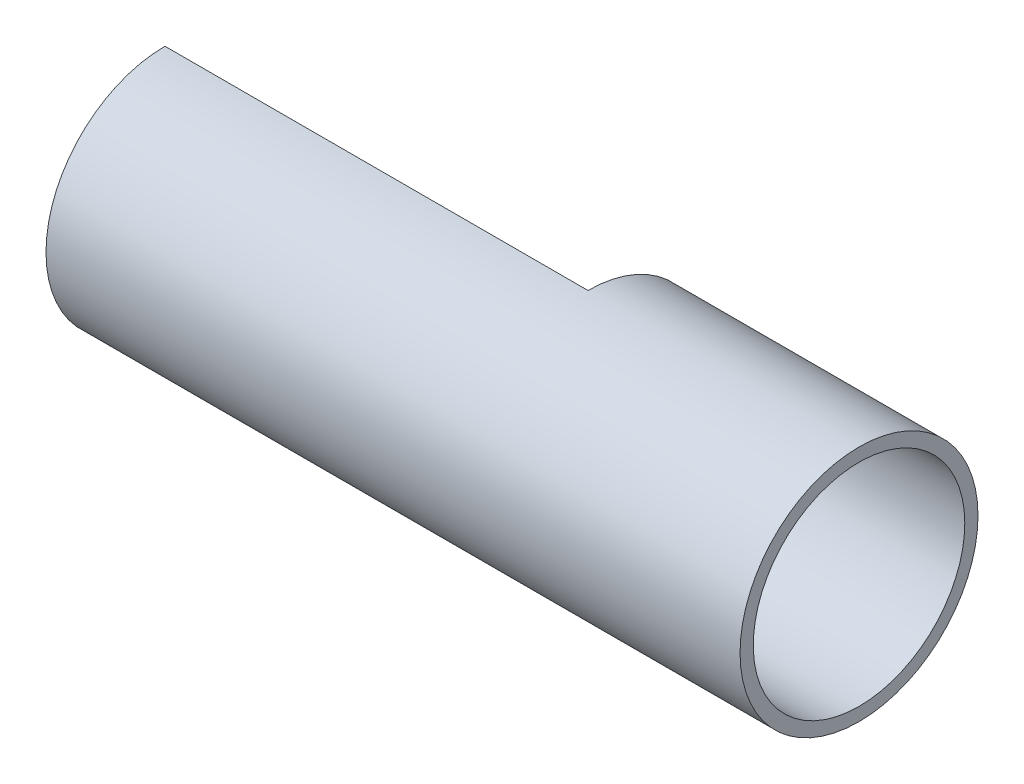
SolidWorks part; units mm, degrees
material "PET"
ref_plane "Front Plane" through (0, 0, 0) normal (0, 0, 1) x (1, 0, 0)
ref_plane "Top Plane" through (0, 0, 0) normal (0, 1, 0) x (1, 0, 0)
ref_plane "Right Plane" through (0, 0, 0) normal (1, 0, 0) x (0, 0, -1)
ref_axis "Axis1" through (88.99, 0, 0) along (-1, 0, 0)
sketch "Sketch1" plane through (0, 0, 0) normal (1, 0, 0) x (0, 0, -1)
  circle A0 centre (0, 0) radius 11.43
  dimension "D1" = 22.86
extrude "Main Shaft" add sketch "Sketch1" along normal mid plane 66.675
sketch "Sketch3" plane through (-33.3375, 0, 0) normal (-1, 0, 0) x (0, 0, 1)
  circle A0 centre (0, 0) radius 6.35
  dimension "D1" = 12.7
sketch "Sketch4" plane through (0, 0, 0) normal (0, 0, 1) x (1, 0, 0)
  line L0 (-33.3375, 6.35) -> (-33.3375, -6.35) construction
  line L1 (-33.3375, 0) -> (-33.3375, 6.35)
  line L2 (-39.6875, 0) -> (-33.3375, 0)
  arc A0 (-33.3375, 6.35) -> (-39.6875, 0) centre (-33.3375, 0) ccw
  dimension "D1" = 6.35
revolve "Bumpout" add sketch "Sketch4" angle 360 about axis through (88.99, 0, 0) along (-1, 0, 0)
sketch "Sketch5" plane through (-33.3375, 0, 0) normal (-1, 0, 0) x (0, 0, 1)
  circle A0 centre (0, 0) radius 1.27
  dimension "D1" = 2.54
extrude "Needle Hole" cut sketch "Sketch5" along normal through all both and the other way through all
ref_plane "Plane1" through (-30.7975, 0, 0) normal (-1, 0, 0) x (0, 0, 1)
sketch "Sketch7" plane through (-30.7975, 0, 0) normal (-1, 0, 0) x (0, 0, 1)
  circle A0 centre (0, 0) radius 10.16
  circle A1 centre (0, 0) radius 11.43 construction
  dimension "D1" = 1.27
extrude "Syringe Slot" cut sketch "Sketch7" against normal blind 40.132
sketch "Sketch9" plane through (33.3375, 0, 0) normal (1, 0, 0) x (0, 0, -1)
  circle A0 centre (0, 0) radius 10.16
  circle A2 centre (0, 0) radius 11.43 construction
  dimension "D1" = 1.27
  dimension "D2" = 20.32
extrude "Spring Slot" cut sketch "Sketch9" against normal offset from surface (22.733 mm away) 1.27 up to face at (9.3345, 0, 1.27)
sketch "Sketch11" plane through (10.6045, 0, 0) normal (1, 0, 0) x (0, 0, -1)
  line L0 (0, 12.573) -> (0, -12.573) construction
  line L1 (0, 0) -> (-1.27, 0) construction
  line L2 (-1.27, 8.7988) -> (-1.27, 0) construction
  line L3 (-1.27, 0) -> (-1.27, -8.7988) construction
  line L4 (-1.27, 8.7988) -> (-1.4514, 10.0558)
  line L5 (1.27, 8.7988) -> (1.4514, 10.0558)
  line L6 (-1.4514, -10.0558) -> (-1.27, -8.7988)
  line L7 (1.27, -8.7988) -> (1.4514, -10.0558)
  arc A0 (-1.4514, 10.0558) -> (-1.4514, -10.0558) centre (0, 0) ccw
  arc A1 (-1.27, 8.7988) -> (-1.27, -8.7988) centre (0, 0) ccw
  circle A2 centre (0, 0) radius 8.89
  circle A3 centre (0, 0) radius 8.89 construction
  arc A4 (1.27, 8.7988) -> (1.27, -8.7988) centre (0, 0) cw
  arc A5 (1.4514, 10.0558) -> (1.4514, -10.0558) centre (0, 0) cw
  dimension "D2" = 1.27
  dimension "D1" = 1.27
  dimension "D3" = 1.27
  dimension "D4" = 1.27
extrude "Tabs" cut sketch "Sketch11" against normal up to surface (1.27 mm away) up to face at (9.3345, 0, 1.27)
sketch "Sketch12" plane through (0, 0, 0) normal (0, 0, 1) x (1, 0, 0)
  line L0 (-33.3375, -11.43) -> (33.3375, -11.43) construction
  line L1 (-33.3375, 11.43) -> (7.3025, 11.43)
  line L2 (-33.3375, 11.43) -> (-33.3375, -11.43)
  line L3 (-33.3375, -11.43) -> (7.3025, -11.43)
  line L4 (7.3025, 11.43) -> (7.3025, -11.43)
  dimension "D1" = 40.64
extrude "Syringe Insert" cut sketch "Sketch12" against normal through all
